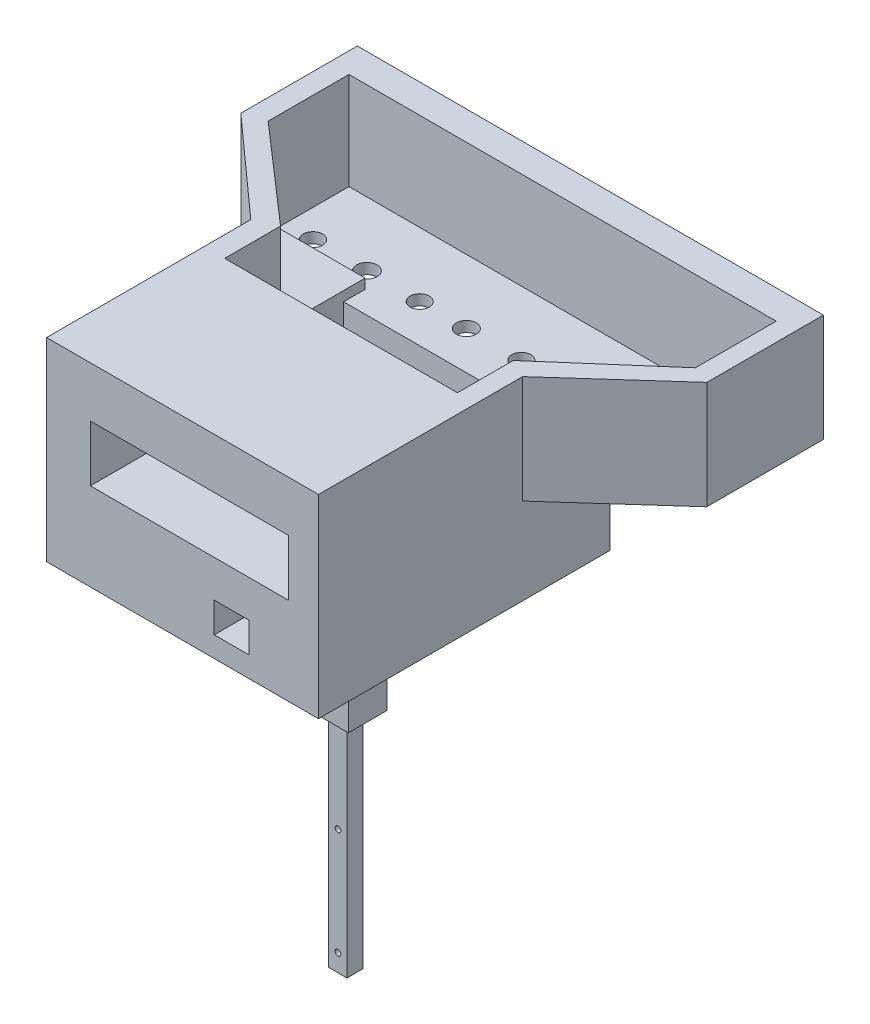
SolidWorks part; units mm, degrees
ref_plane "前视基准面" through (0, 0, 0) normal (0, 0, 1) x (1, 0, 0)
ref_plane "上视基准面" through (0, 0, 0) normal (0, 1, 0) x (1, 0, 0)
ref_plane "右视基准面" through (0, 0, 0) normal (1, 0, 0) x (0, 0, -1)
other "Configuration Table"
sketch "草图8" plane through (0, 0, 0) normal (0, 1, 0) x (1, 0, 0)
  line L1 (-68.2051, 97.4231) -> (71.7949, 97.4231)
  line L2 (-68.2051, 97.4231) -> (-68.2051, -32.5769)
  line L3 (-68.2051, -32.5769) -> (71.7949, -32.5769)
  line L4 (71.7949, 97.4231) -> (71.7949, -32.5769)
  dimension "D1" = 140
  dimension "D2" = 130
extrude "凸台-拉伸2" add sketch "草图8" along normal blind 100
sketch "草图9" plane through (0, 100, 0) normal (0, 1, 0) x (1, 0, 0)
  line L1 (-57.6643, 89.8112) -> (62.1893, 89.8112)
  line L2 (-57.6643, 89.8112) -> (-57.6643, -24.4306)
  line L3 (-57.6643, -24.4306) -> (62.1893, -24.4306)
  line L4 (62.1893, 89.8112) -> (62.1893, -24.4306)
extrude "切除-拉伸2" cut sketch "草图9" against normal blind 90
sketch "草图10" plane through (0, 0, -97.4231) normal (0, 0, -1) x (-1, 0, 0)
  line L0 (-71.7949, 100) -> (-71.7949, 0) construction
  line L5 (-71.7949, 100) -> (68.2051, 100)
  line L6 (-71.7949, 100) -> (-71.7949, 44.5494)
  line L7 (-71.7949, 44.5494) -> (68.2051, 44.5494)
  line L8 (68.2051, 100) -> (68.2051, 44.5494)
  line L9 (-71.7949, 100) -> (68.2051, 100) construction
  line L10 (68.2051, 100) -> (68.2051, 0) construction
extrude "凸台-拉伸3" add sketch "草图10" along normal blind 60
sketch "草图11" plane through (0, 100, 0) normal (0, 1, 0) x (1, 0, 0)
  line L1 (-57.6643, 89.8112) -> (62.1893, 89.8112)
  line L2 (-57.6643, 89.8112) -> (-57.6643, 142.577)
  line L3 (-57.6643, 142.577) -> (62.1893, 142.577)
  line L4 (62.1893, 89.8112) -> (62.1893, 142.577)
extrude "切除-拉伸3" cut sketch "草图11" against normal blind 50
sketch "草图12" plane through (-68.2051, 0, 0) normal (-1, 0, 0) x (0, 0, 1)
  line L1 (-97.4231, 44.5494) -> (-157.4231, 44.5494)
  line L2 (-97.4231, 44.5494) -> (-97.4231, 100)
  line L3 (-97.4231, 100) -> (-157.4231, 100)
  line L4 (-157.4231, 44.5494) -> (-157.4231, 100)
extrude "凸台-拉伸4" add sketch "草图12" along normal blind 50
sketch "草图13" plane through (71.7949, 0, 0) normal (1, 0, 0) x (0, 0, -1)
  line L1 (97.4231, 44.5494) -> (157.4231, 44.5494)
  line L2 (97.4231, 44.5494) -> (97.4231, 100)
  line L3 (97.4231, 100) -> (157.4231, 100)
  line L4 (157.4231, 44.5494) -> (157.4231, 100)
extrude "凸台-拉伸5" add sketch "草图13" along normal blind 50
sketch "草图15" plane through (-57.6643, 0, 0) normal (1, 0, 0) x (0, 0, -1)
  line L0 (142.577, 100) -> (-24.4306, 100) construction
  line L1 (100.9594, 100) -> (142.577, 100)
  line L2 (100.9594, 100) -> (100.9594, 50)
  line L3 (100.9594, 50) -> (142.577, 50)
  line L4 (142.577, 100) -> (142.577, 50)
extrude "切除-拉伸5" cut sketch "草图15" against normal blind 50 contours L2 L1 L4 L3
sketch "草图16" plane through (-107.6643, 0, 0) normal (1, 0, 0) x (0, 0, -1)
  line L0 (100.9594, 100) -> (100.9594, 50) construction
  line L1 (100.9594, 100) -> (142.577, 100)
  line L2 (100.9594, 100) -> (100.9594, 50.0594)
  line L3 (100.9594, 50.0594) -> (142.577, 50.0594)
  line L4 (142.577, 100) -> (142.577, 50.0594)
  line L5 (142.577, 100) -> (142.577, 50) construction
extrude "切除-拉伸6" cut sketch "草图16" along normal blind 220
sketch "草图17" plane through (0, 0, 0) normal (0, -1, 0) x (-1, 0, 0)
  line L0 (0, 79.8702) -> (0, 147.4019) construction
  line L1 (0, 79.8702) -> (0, 147.4019) construction
  line L2 (91.4759, 0) -> (-94.8516, 0) construction
  line L3 (0, -58.6423) -> (0, 79.8702) construction
  line L4 (0, 147.4019) -> (0, 174.5679) construction
  line L7 (44.2061, 0) -> (44.2061, -45.2254)
  line L8 (44.2061, -45.2254) -> (-43.7939, -45.2254)
  line L9 (-43.7939, -45.2254) -> (-43.7939, 0)
  line L10 (44.2061, 0) -> (44.2061, 50.7746)
  line L11 (44.2061, 50.7746) -> (-43.7939, 50.7746)
  line L12 (-43.7939, 50.7746) -> (-43.7939, 0)
sketch "草图18" plane through (0, 0, 32.5769) normal (0, 0, 1) x (1, 0, 0)
  line L0 (-68.2051, 100) -> (-68.2051, 0) construction
  line L1 (-68.2051, 100) -> (71.7949, 100)
  line L2 (-68.2051, 100) -> (-68.2051, 0)
  line L3 (-68.2051, 0) -> (71.7949, 0)
  line L4 (71.7949, 100) -> (71.7949, 0)
extrude "凸台-拉伸6" add sketch "草图18" along normal blind 20
sketch "草图19" plane through (0, 0, 24.4306) normal (0, 0, -1) x (-1, 0, 0)
  line L1 (-62.1893, 100) -> (57.6643, 100)
  line L2 (-62.1893, 100) -> (-62.1893, 10)
  line L3 (-62.1893, 10) -> (57.6643, 10)
  line L4 (57.6643, 100) -> (57.6643, 10)
extrude "切除-拉伸7" cut sketch "草图19" against normal blind 17
sketch "草图20" plane through (0, 0, 0) normal (0, -1, 0) x (1, 0, 0)
  line L4 (-42.9977, -75) -> (-22.9977, -75)
  line L5 (-22.9977, -85) -> (-42.9977, -85)
  line L6 (22.9977, -85) -> (42.9977, -85)
  line L7 (42.9977, -75) -> (22.9977, -75)
  arc A0 (-42.9977, -75) -> (-42.9977, -85) centre (-42.9977, -80) ccw
  arc A1 (-22.9977, -85) -> (-22.9977, -75) centre (-22.9977, -80) ccw
  arc A2 (22.9977, -85) -> (22.9977, -75) centre (22.9977, -80) cw
  arc A3 (42.9977, -75) -> (42.9977, -85) centre (42.9977, -80) cw
extrude "切除-拉伸8" cut sketch "草图20" against normal blind 17
sketch "草图27" plane through (0, 44.5494, 0) normal (0, -1, 0) x (-1, 0, 0)
  circle A0 centre (14.1554, 109.5257) radius 5
  circle A4 centre (38.1746, 109.5257) radius 5
  circle A7 centre (65.5117, 109.6572) radius 5
  circle A10 centre (93.3099, 109.6572) radius 5
sketch "草图28" plane through (0, 44.5494, 0) normal (0, -1, 0) x (1, 0, 0)
  circle A0 centre (-93.3099, -109.6572) radius 5.0044
  circle A1 centre (-65.5117, -109.6572) radius 5.0989
  circle A2 centre (-38.1746, -109.5257) radius 5.054
  circle A3 centre (-14.1554, -109.5257) radius 5.043
  circle A4 centre (14.1554, -109.5257) radius 5.043
  circle A5 centre (38.1746, -109.5257) radius 5.054
  circle A6 centre (65.5117, -109.6572) radius 5.0989
  circle A7 centre (93.3099, -109.6572) radius 5.0044
sketch "草图29" plane through (0, 44.5494, 0) normal (0, -1, 0) x (1, 0, 0)
  circle A0 centre (-93.3099, -109.6572) radius 5.0135
  circle A1 centre (-65.5117, -109.6572) radius 5.2498
  circle A2 centre (-38.1746, -109.5257) radius 4.9384
  circle A3 centre (-14.1554, -109.5257) radius 5.1047
  circle A4 centre (14.1554, -109.5257) radius 4.9426
  circle A5 centre (38.1746, -109.5257) radius 5.2184
  circle A6 centre (65.5117, -109.6572) radius 5.1093
  circle A7 centre (93.3099, -109.6572) radius 4.8467
extrude "切除-拉伸9" cut sketch "草图29" against normal blind 17
sketch "草图34" plane through (0, 0, 0) normal (0, -1, 0) x (1, 0, 0)
extrude "凸台-拉伸9" add sketch "草图17" along normal blind 4
sketch "草图37" plane through (0, -4, 0) normal (0, -1, 0) x (1, 0, 0)
  line L0 (-44.2061, 45.2254) -> (-46.2061, 45.2254)
  line L1 (-46.2061, 45.2254) -> (-46.2061, -50.7746)
  line L2 (-46.2061, -50.7746) -> (-44.2061, -50.7746)
  line L3 (43.7939, 45.2254) -> (45.7939, 45.2254)
  line L4 (45.7939, 45.2254) -> (45.7939, -50.7746)
  line L5 (45.7939, -50.7746) -> (43.7939, -50.7746)
  line L6 (-44.2061, 45.2254) -> (-44.2061, -50.7746)
  line L7 (43.7939, 45.2254) -> (43.7939, -50.7746)
extrude "凸台-拉伸10" add sketch "草图37" against normal blind 4
sketch "草图39" plane through (0, -4, 0) normal (0, -1, 0) x (1, 0, 0)
  line L2 (-42, -50.7746) -> (-42, 43.3321)
  line L3 (-46.2061, -50.7746) -> (45.7939, -50.7746) construction
  line L4 (-42, 43.3321) -> (42, 43.3321)
  line L5 (42, 43.3321) -> (42, -50.7746)
  line L6 (42, -50.7746) -> (-42, -50.7746)
extrude "切除-拉伸10" cut sketch "草图39" against normal blind 4
sketch "草图40" plane through (0, 0, -50.7746) normal (0, 0, -1) x (-1, 0, 0)
  line L1 (42, 0) -> (44.323, 0)
  line L2 (42, 0) -> (42, -2.0813)
  line L3 (42, -2.0813) -> (44.323, -2.0813)
  line L4 (44.323, 0) -> (44.323, -2.0813)
extrude "切除-拉伸12" cut sketch "草图40" against normal blind 94
sketch "草图42" plane through (0, 0, -50.7746) normal (0, 0, -1) x (-1, 0, 0)
  line L0 (-71.7949, 0) -> (68.2051, 0) construction
  line L1 (-42, 0) -> (-44.0954, 0)
  line L2 (-42, 0) -> (-42, -1.9582)
  line L3 (-42, -1.9582) -> (-44.0954, -1.9582)
  line L4 (-44.0954, 0) -> (-44.0954, -1.9582)
  line L5 (-42, 0) -> (-45.7939, 0) construction
extrude "切除-拉伸13" cut sketch "草图42" against normal blind 94
sketch "草图43" plane through (0, 0, 0) normal (0, -1, 0) x (1, 0, 0)
  line L3 (50.1433, 25.8553) -> (59.7626, 25.8553)
  line L4 (50.1433, 25.8553) -> (50.1433, 17.7254)
  line L5 (50.1433, 17.7254) -> (59.7626, 17.7254)
  line L6 (59.7626, 25.8553) -> (59.7626, 17.7254)
extrude "凸台-拉伸11" add sketch "草图43" along normal blind 135
sketch "草图44" plane through (0, 0, 17.7254) normal (0, 0, -1) x (-1, 0, 0)
  circle A0 centre (-55.0954, -71) radius 1.5
  circle A1 centre (-55.0954, -127) radius 1.5
  dimension "D1" = 3
extrude "切除-拉伸14" cut sketch "草图44" against normal blind 40
sketch "草图45" plane through (0, 0, 0) normal (0, -1, 0) x (1, 0, 0)
  line L0 (45.7939, -50.7746) -> (45.7939, 45.2254) construction
  line L1 (45.7939, 31.1512) -> (65.7634, 31.1512)
  line L2 (45.7939, 31.1512) -> (45.7939, 11.3123)
  line L3 (45.7939, 11.3123) -> (65.7634, 11.3123)
  line L4 (65.7634, 31.1512) -> (65.7634, 11.3123)
extrude "凸台-拉伸12" add sketch "草图45" along normal blind 20
sketch "草图46" plane through (0, 100, 0) normal (0, 1, 0) x (1, 0, 0)
  line L0 (-118.2051, 97.4231) -> (-68.2051, 52.5704)
  line L1 (-68.2051, 97.4231) -> (-68.2051, -52.5769) construction
  line L2 (-118.2051, 97.4231) -> (-68.2051, 97.4231)
  line L3 (-118.2051, 97.4231) -> (-68.2051, 97.4231) construction
  line L4 (-68.2051, 97.4231) -> (-68.2051, 52.5704)
  line L5 (71.7949, 97.4231) -> (71.7949, 52.5704)
  line L6 (71.7949, -52.5769) -> (71.7949, 97.4231) construction
  line L7 (71.7949, 52.5704) -> (121.7949, 97.4231)
  line L8 (121.7949, 97.4231) -> (71.7949, 97.4231)
extrude "凸台-拉伸13" add sketch "草图46" against normal blind 55.5
sketch "草图47" plane through (0, 100, 0) normal (0, 1, 0) x (1, 0, 0)
  line L0 (-107.6643, 100.9594) -> (-57.6643, 57.3447)
  line L1 (-57.6643, 100.9594) -> (-57.6643, -41.4306) construction
  line L2 (-57.6643, 57.3447) -> (-57.6643, 100.9594)
  line L3 (-57.6643, 100.9594) -> (-107.6643, 100.9594)
  line L4 (112.3357, 100.9594) -> (62.1893, 57.3447)
  line L5 (62.1893, -41.4306) -> (62.1893, 89.8112) construction
  line L6 (62.1893, 57.3447) -> (62.1893, 100.9594)
  line L7 (62.1893, 89.8112) -> (62.1893, 105.7756) construction
  line L8 (112.3357, 100.9594) -> (62.1893, 100.9594) construction
  line L9 (62.1893, 100.9594) -> (112.3357, 100.9594)
extrude "切除-拉伸15" cut sketch "草图47" against normal blind 45
sketch "草图50" plane through (0, 10, 0) normal (0, 1, 0) x (1, 0, 0)
  line L0 (62.1893, -41.4306) -> (62.1893, 57.3447) construction
  line L1 (-57.6643, -41.4306) -> (62.1893, -41.4306)
  line L2 (-57.6643, -41.4306) -> (-57.6643, 28.5694)
  line L3 (-57.6643, 28.5694) -> (62.1893, 28.5694)
  line L4 (62.1893, -41.4306) -> (62.1893, 28.5694)
  dimension "D1" = 70
extrude "凸台-拉伸14" add sketch "草图50" along normal blind 90
sketch "草图51" plane through (0, 0, 52.5769) normal (0, 0, 1) x (1, 0, 0)
  line L1 (-45.6972, 82.0464) -> (56.3833, 82.0464)
  line L2 (-45.6972, 82.0464) -> (-45.6972, 45.1024)
  line L3 (-45.6972, 45.1024) -> (56.3833, 45.1024)
  line L4 (56.3833, 82.0464) -> (56.3833, 45.1024)
extrude "切除-拉伸17" cut sketch "草图51" against normal blind 70
sketch "草图52" plane through (0, 82.0464, 0) normal (0, -1, 0) x (1, 0, 0)
  line L0 (56.3833, 52.5769) -> (-45.6972, 52.5769) construction
  line L1 (-45.6972, 52.5769) -> (56.8746, 52.5769)
  line L2 (-45.6972, 52.5769) -> (-45.6972, 49.6801)
  line L3 (-45.6972, 49.6801) -> (56.8746, 49.6801)
  line L4 (56.8746, 52.5769) -> (56.8746, 49.6801)
extrude "凸台-拉伸16" add sketch "草图52" along normal blind 8
sketch "草图54" plane through (0, -4, 0) normal (0, -1, 0) x (1, 0, 0)
  line L0 (45.7939, 45.2254) -> (-46.2061, 45.2254) construction
  line L1 (-32.5025, 45.2254) -> (33.1178, 45.2254)
  line L2 (-32.5025, 45.2254) -> (-32.5025, 43.3321)
  line L3 (-32.5025, 43.3321) -> (33.1178, 43.3321)
  line L4 (33.1178, 45.2254) -> (33.1178, 43.3321)
  line L5 (42, 43.3321) -> (-42, 43.3321) construction
extrude "切除-拉伸18" cut sketch "草图54" against normal blind 4
sketch "草图55" plane through (0, 0, 17.7254) normal (0, 0, -1) x (-1, 0, 0)
  line L1 (-58.241, -122.3391) -> (-51.5877, -122.3391)
  line L2 (-58.241, -122.3391) -> (-58.241, -133.4996)
  line L3 (-58.241, -133.4996) -> (-51.5877, -133.4996)
  line L4 (-51.5877, -122.3391) -> (-51.5877, -133.4996)
extrude "凸台-拉伸17" add sketch "草图55" against normal blind 8
sketch "草图56" plane through (0, 0, 25.8553) normal (0, 0, 1) x (1, 0, 0)
  line L1 (52.8683, -122.9317) -> (57.3187, -122.9317)
  line L2 (52.8683, -122.9317) -> (52.8683, -132.8921)
  line L3 (52.8683, -132.8921) -> (57.3187, -132.8921)
  line L4 (57.3187, -122.9317) -> (57.3187, -132.8921)
extrude "凸台-拉伸18" add sketch "草图56" against normal blind 8
sketch "草图57" plane through (0, 0, 17.7254) normal (0, 0, -1) x (-1, 0, 0)
  circle A0 centre (-55.0954, -126) radius 1.5
extrude "切除-拉伸19" cut sketch "草图57" against normal blind 20
sketch "草图58" plane through (0, 0, 52.5769) normal (0, 0, 1) x (1, 0, 0)
  line L1 (18.1129, 26.0502) -> (35.9145, 26.0502)
  line L2 (18.1129, 26.0502) -> (18.1129, 10.5798)
  line L3 (18.1129, 10.5798) -> (35.9145, 10.5798)
  line L4 (35.9145, 26.0502) -> (35.9145, 10.5798)
extrude "切除-拉伸21" cut sketch "草图58" against normal blind 45
sketch "草图59" plane through (0, 26.0502, 0) normal (0, -1, 0) x (1, 0, 0)
  line L0 (18.1129, 7.5769) -> (18.1129, 52.5769) construction
  line L1 (18.1129, 7.763) -> (35.9145, 7.763)
  line L2 (18.1129, 7.763) -> (18.1129, 21.3271)
  line L3 (18.1129, 21.3271) -> (35.9145, 21.3271)
  line L4 (35.9145, 7.763) -> (35.9145, 21.3271)
  line L5 (35.9145, 7.5769) -> (35.9145, 52.5769) construction
extrude "切除-拉伸22" cut sketch "草图59" against normal blind 25
sketch "草图62" plane through (0, 10.5798, 0) normal (0, 1, 0) x (1, 0, 0)
  line L0 (18.1129, -7.5769) -> (18.1129, -52.5769) construction
  line L1 (18.1129, -12.4944) -> (35.9145, -12.4944)
  line L2 (18.1129, -12.4944) -> (18.1129, -52.5769)
  line L3 (18.1129, -52.5769) -> (35.9145, -52.5769)
  line L4 (35.9145, -12.4944) -> (35.9145, -52.5769)
revolve "切除-旋转1" cut sketch "草图62" angle 45 about L3
